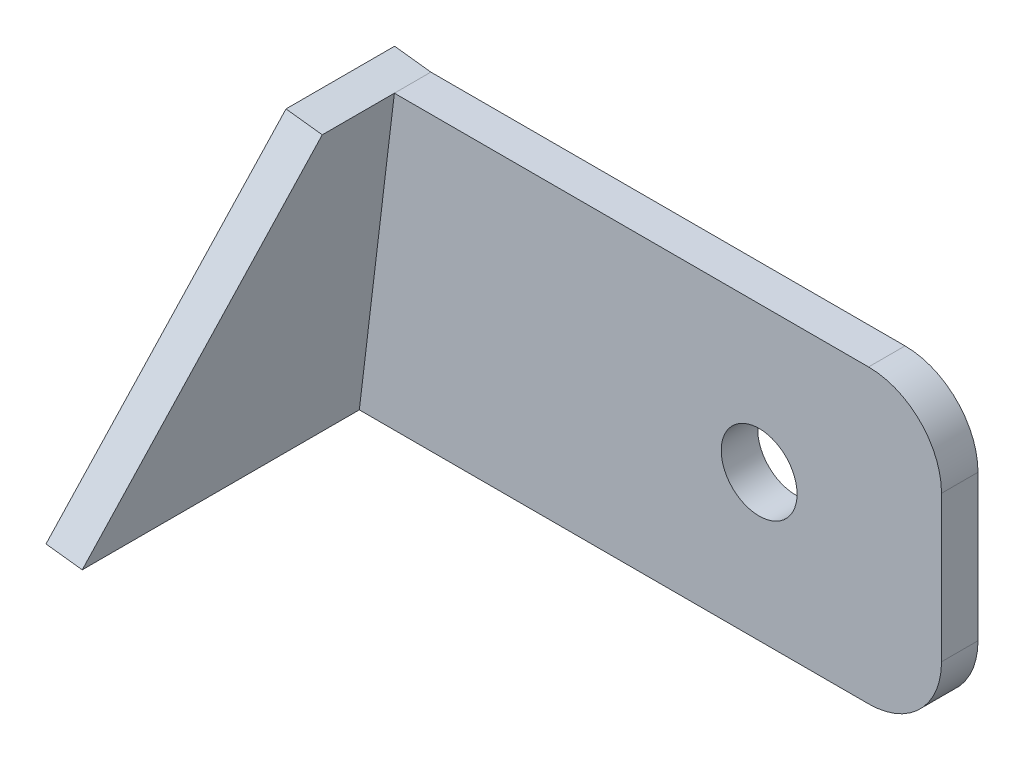
SolidWorks part; units mm, degrees
material "AISI 4130 Steel, annealed at 865C"
ref_plane "Front Plane" through (0, 0, 0) normal (0, 0, 1) x (1, 0, 0)
ref_plane "Top Plane" through (0, 0, 0) normal (0, 1, 0) x (1, 0, 0)
ref_plane "Right Plane" through (0, 0, 0) normal (1, 0, 0) x (0, 0, -1)
sketch "Sketch1" plane through (0, 0, 0) normal (0, 0, 1) x (1, 0, 0)
  line L0 (0, 12.7) -> (-3.0512, -12.7)
  line L1 (0, 12.7) -> (47.625, 12.7)
  line L2 (0, 12.7) -> (0, -12.7) construction
  line L3 (0, -12.7) -> (47.625, -12.7)
  line L4 (47.625, 12.7) -> (47.625, -12.7)
  line L5 (23.8125, -12.7) -> (23.8125, 12.7) construction
  line L6 (0, 0) -> (47.625, 0) construction
  line L7 (-3.0512, -12.7) -> (0, -12.7)
  line L8 (-2.2863, -6.3323) -> (-5.4386, -5.9536)
  line L9 (-5.4386, -5.9536) -> (-3.9173, 6.711)
  line L10 (-3.9173, 6.711) -> (-0.7649, 6.3323)
  line L11 (-0.7801, 6.2062) -> (-3.9324, 6.5849)
  line L12 (-2.2712, -6.2062) -> (-5.4235, -5.8275)
  point P168 (23.8125, 0)
  dimension "D1" = 25.4
  dimension "D2" = 47.625
  dimension "D3" = 83.15
  dimension "D4" = 3.175
  dimension "D5" = 6.4135
  dimension "D6" = 6.4135
  dimension "D7" = 0.127
  dimension "D8" = 0.127
extrude "Boss-Extrude1" add sketch "Sketch1" along normal blind 3.175 contours L0 L7 L3 L4 L1 | L12 L0 L11 L9
sketch "Sketch3" plane through (0, 0, 3.175) normal (0, 0, 1) x (1, 0, 0)
  line L0 (0, 0) -> (31.75, 0) construction
  circle A0 centre (31.75, 0) radius 3.302
  dimension "D1" = 6.604
  dimension "D2" = 31.75
extrude "Cut-Extrude1" cut sketch "Sketch3" against normal through all both and the other way through all contours A0
sketch "Sketch2" plane through (-1.5039, 0.1807, 0) normal (-0.9929, 0.1193, 0) x (0, 0, 1)
  line L0 (0, 6.1958) -> (3.175, 6.1958)
  line L5 (0, 12.6093) -> (0, -12.9733)
  line L6 (0, -12.9733) -> (27.2953, -12.9733)
  line L9 (0, 12.6093) -> (9.4538, 12.6093)
  line L10 (9.4538, 12.6093) -> (27.2953, -12.9733)
  line L11 (3.175, 6.1958) -> (3.175, -6.5598)
  line L12 (3.175, -6.5598) -> (0, -6.5598)
  line M3 (0, -12.9733) -> (3.175, -12.9733)
  line M14 (3.175, -12.9733) -> (3.175, -6.4328)
  dimension "D1" = 3.175
  dimension "D2" = 6.4135
  dimension "D3" = 6.4135
  dimension "D4" = 27.2953
  dimension "D5" = 9.4538
extrude "Boss-Extrude2" add sketch "Sketch2" along normal blind 3.175 separate body contours L12 L5 M14 M3 | L0 L11 L6 L10 L9 L5 M14
fillet "Fillet1" radius 6.35 2 edges at (47.625, -12.7, 1.5875) (47.625, 12.7, 1.5875)
